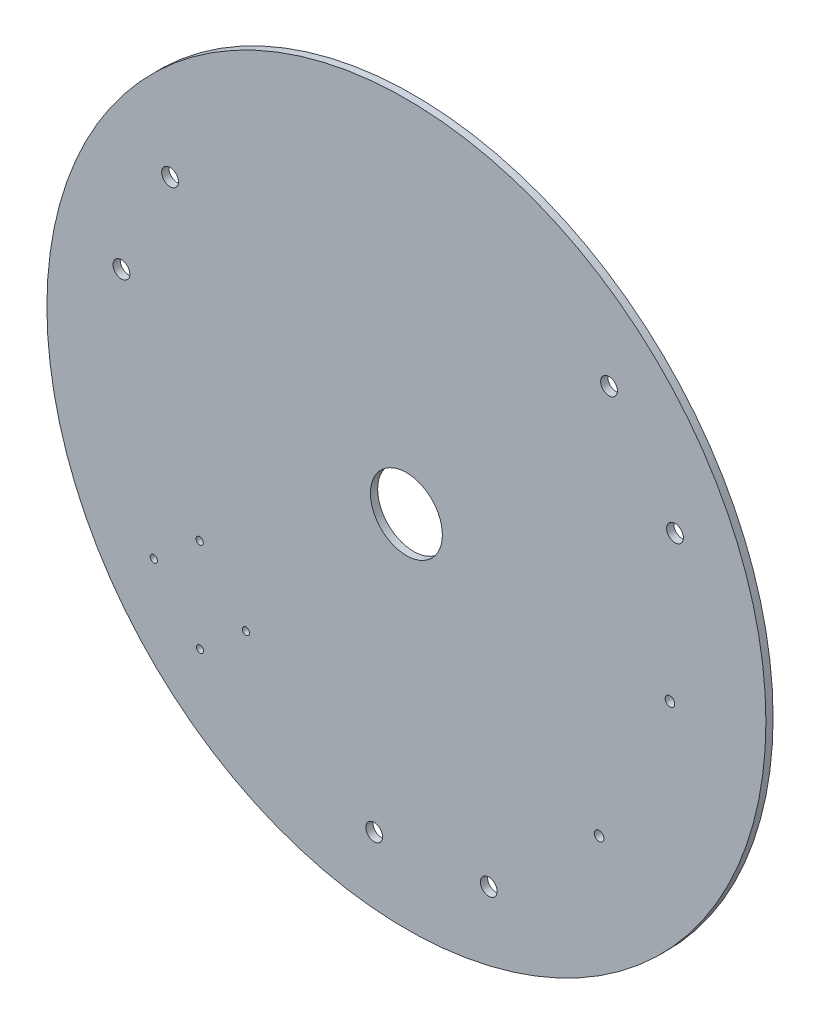
SolidWorks part; units mm, degrees
ref_plane "Front Plane" through (0, 0, 0) normal (0, 0, 1) x (1, 0, 0)
ref_plane "Top Plane" through (0, 0, 0) normal (0, 1, 0) x (1, 0, 0)
ref_plane "Right Plane" through (0, 0, 0) normal (1, 0, 0) x (0, 0, -1)
sketch "Sketch1" plane through (0, 0, 0) normal (0, 0, 1) x (1, 0, 0)
  circle A0 centre (0, 0) radius 150
  dimension "D1" = 300
extrude "Boss-Extrude1" add sketch "Sketch1" along normal blind 3
sketch "Sketch2" plane through (0, 0, 0) normal (0, 0, -1) x (-1, 0, 0)
  line L0 (0, 0) -> (0, 199.4542) construction
  line L1 (0, 0) -> (-183.0223, 128.1536) construction
  line L6 (-84.5324, 88.4888) -> (-112.0641, 49.1695) construction
  circle A0 centre (-84.5324, 88.4888) radius 3.5
  circle A1 centre (-112.0641, 49.1695) radius 3.5
  dimension "D6" = 7
  dimension "D1" = 55
  dimension "D2" = 24
  dimension "D3" = 120
extrude "Cut-Extrude1" cut sketch "Sketch2" against normal up to surface (3 mm away) up to face at (150, 0, 3)
pattern_circular "CirPattern1" count 3 over 360 about axis through (0, 0, 0) along (0, 0, 1) of "Cut-Extrude1"
sketch "Sketch3" plane through (0, 0, 0) normal (0, 0, -1) x (-1, 0, 0)
  line L0 (0, 0) -> (-135.9462, -63.3927) construction
  line L1 (-80.3707, -76.0957) -> (-109.954, -12.6541) construction
  line L2 (-84.5324, 88.4888) -> (-112.0641, 49.1695) construction
  line L4 (0, 0) -> (-98.2982, 68.8292) construction
  circle A0 centre (0, 0) radius 150 construction
  circle A1 centre (-109.954, -12.6541) radius 2
  circle A2 centre (-80.3707, -76.0957) radius 2
  dimension "D1" = 4
  dimension "D2" = 4
  dimension "D5" = 60
  dimension "D3" = 35
  dimension "D4" = 45
extrude "Cut-Extrude2" cut sketch "Sketch3" against normal up to surface (3 mm away) up to face at (37.8674, -117.4516, 3)
sketch "Sketch4" plane through (0, 0, 0) normal (0, 0, -1) x (-1, 0, 0)
  circle A0 centre (0, 0) radius 15
  dimension "D1" = 30
extrude "Cut-Extrude3" cut sketch "Sketch4" against normal up to surface (3 mm away) up to face at (111.954, -12.6541, 3)
sketch "Sketch6" plane through (0, 0, 0) normal (0, 0, -1) x (-1, 0, 0)
  line L0 (66.9626, -75.7694) -> (86.2463, -52.7881) construction
  line L2 (-34.3674, -117.4516) -> (13.45, -121.6351) construction
  line L4 (0, 0) -> (-10.4587, -119.5434) construction
  line L5 (0, 0) -> (146.4579, -122.8927) construction
  circle A4 centre (66.9626, -75.7694) radius 1.5
  circle A5 centre (86.1137, -91.8391) radius 1.5
  circle A6 centre (105.3974, -68.8578) radius 1.5
  circle A7 centre (86.2463, -52.7881) radius 1.5
  dimension "D2" = 3
  dimension "D3" = 3
  dimension "D4" = 3
  dimension "D5" = 3
  dimension "D6" = 15
  dimension "D7" = 15
  dimension "D8" = 25
  dimension "D9" = 100
  dimension "D10" = 55
extrude "Cut-Extrude5" cut sketch "Sketch6" against normal up to surface (3 mm away) up to face at (15, 0, 3)
